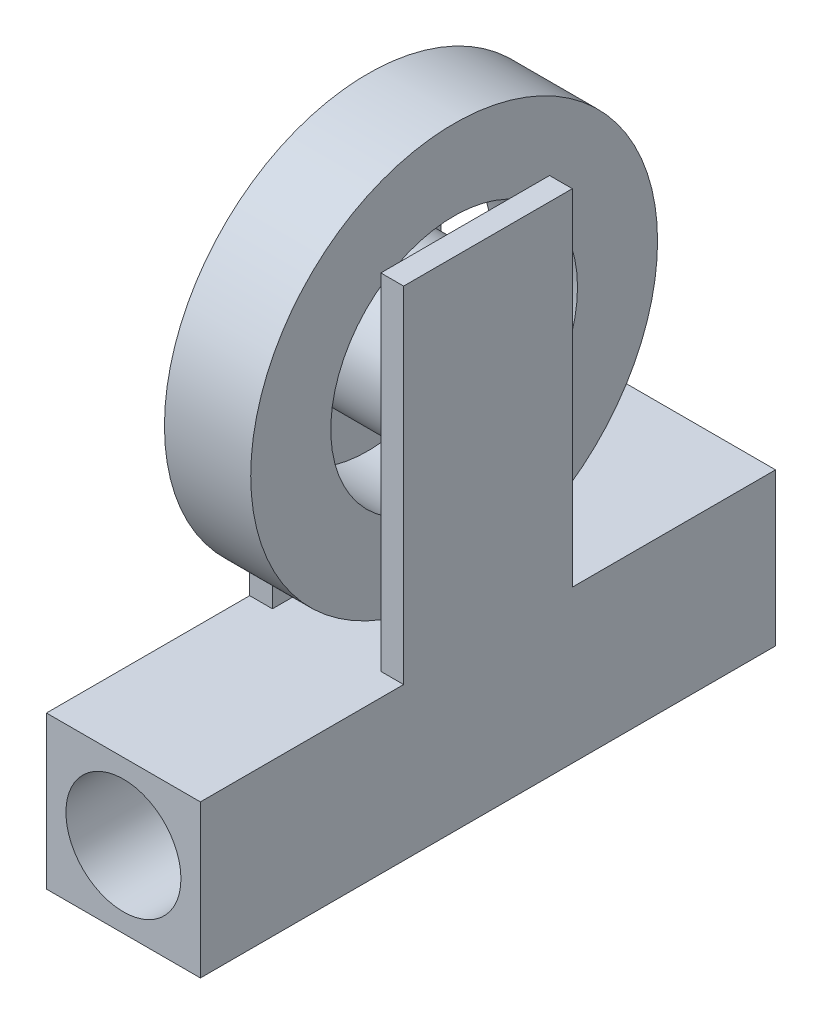
SolidWorks part; units mm, degrees
ref_plane "Front Plane" through (0, 0, 0) normal (0, 0, 1) x (1, 0, 0)
ref_plane "Top Plane" through (0, 0, 0) normal (0, 1, 0) x (1, 0, 0)
ref_plane "Right Plane" through (0, 0, 0) normal (1, 0, 0) x (0, 0, -1)
sketch "Sketch1" plane through (0, 0, 0) normal (0, 0, 1) x (1, 0, 0)
  line L1 (-13.3845, 13.2594) -> (13.3845, 13.2594)
  line L2 (-13.3845, 13.2594) -> (-13.3845, -13.2594)
  line L3 (-13.3845, -13.2594) -> (13.3845, -13.2594)
  line L4 (13.3845, 13.2594) -> (13.3845, -13.2594)
  line L5 (-13.3845, 13.2594) -> (13.3845, -13.2594) construction
  line L6 (-13.3845, -13.2594) -> (13.3845, 13.2594) construction
  circle A0 centre (0, 0) radius 10
  point P0 (0, 0)
extrude "Boss-Extrude1" add sketch "Sketch1" along normal blind 100
sketch "Sketch2" plane through (0, 13.2594, 0) normal (0, 1, 0) x (1, 0, 0)
  line L0 (-13.3845, -35.3346) -> (-13.3845, -64.6654)
  line L1 (-13.3845, -100) -> (-13.3845, 0) construction
  line L2 (-13.3845, -64.6654) -> (-9.4237, -64.6654)
  line L3 (-9.4237, -64.6654) -> (-9.4237, -35.3346)
  line L4 (-9.4237, -35.3346) -> (-13.3845, -35.3346)
  line L5 (0, -14.5853) -> (0, 14.5853) construction
  line L6 (9.4237, -35.3346) -> (13.3845, -35.3346)
  line L7 (9.4237, -64.6654) -> (9.4237, -35.3346)
  line L8 (13.3845, -64.6654) -> (9.4237, -64.6654)
  line L9 (13.3845, -35.3346) -> (13.3845, -64.6654)
  point P5 (-13.3845, -50)
  point P13 (13.3845, -50)
extrude "Boss-Extrude2" add sketch "Sketch2" along normal blind 60
sketch "Sketch3" plane through (13.3845, 0, 0) normal (1, 0, 0) x (0, 0, -1)
  circle A0 centre (-50, 52.0991) radius 12.7427
  point P2 (0, 0)
extrude "Boss-Extrude3" add sketch "Sketch3" against normal up to surface (22.8082 mm away) up to face at (-9.4237, 43.2594, 50)
sketch "Sketch4" plane through (0, 0, 0) normal (1, 0, 0) x (0, 0, -1)
  circle A0 centre (-50, 52.0991) radius 35.3684
  circle A1 centre (-50, 52.0991) radius 21.4506
extrude "Boss-Extrude4" add sketch "Sketch4" along normal mid plane 15 separate body
